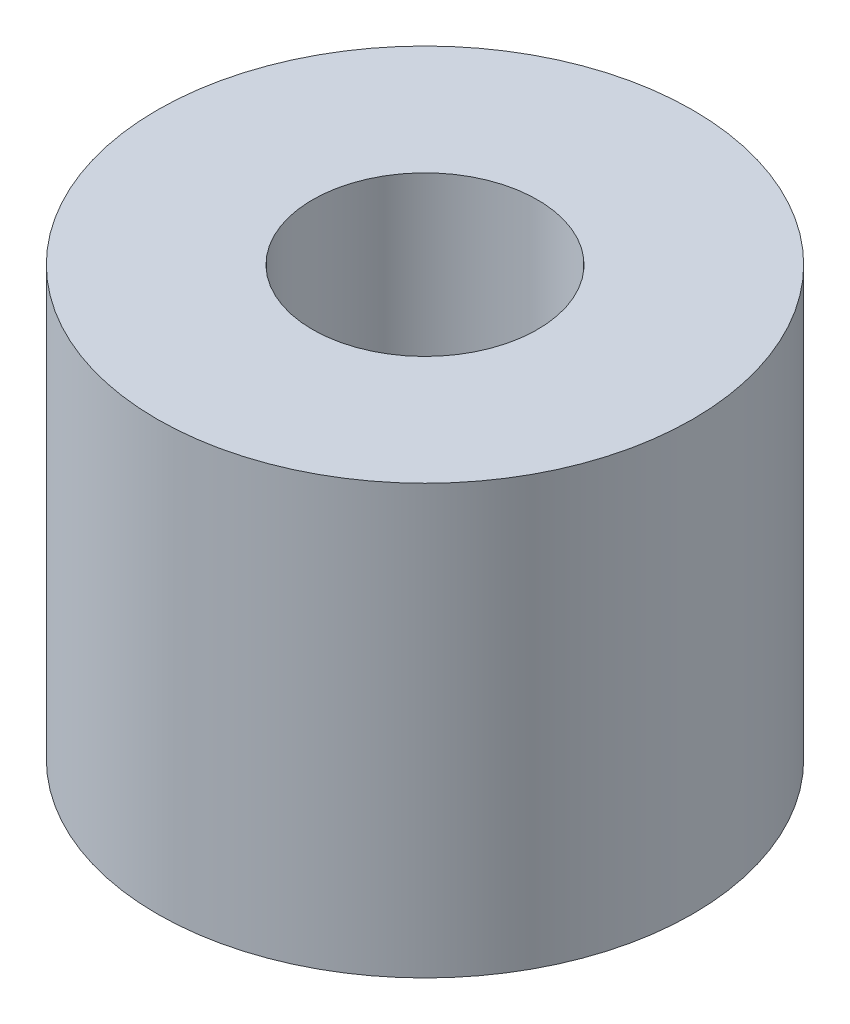
SolidWorks part; units mm, degrees
ref_plane "Front Plane" through (0, 0, 0) normal (0, 0, 1) x (1, 0, 0)
ref_plane "Top Plane" through (0, 0, 0) normal (0, 1, 0) x (1, 0, 0)
ref_plane "Right Plane" through (0, 0, 0) normal (1, 0, 0) x (0, 0, -1)
sketch "Sketch1" plane through (0, 0, 0) normal (0, 1, 0) x (1, 0, 0)
  circle A0 centre (0, 0) radius 2.1
  circle A1 centre (0, 0) radius 5
  dimension "D1" = 4.2
  dimension "D2" = 10
extrude "Boss-Extrude1" add sketch "Sketch1" along normal blind 8
